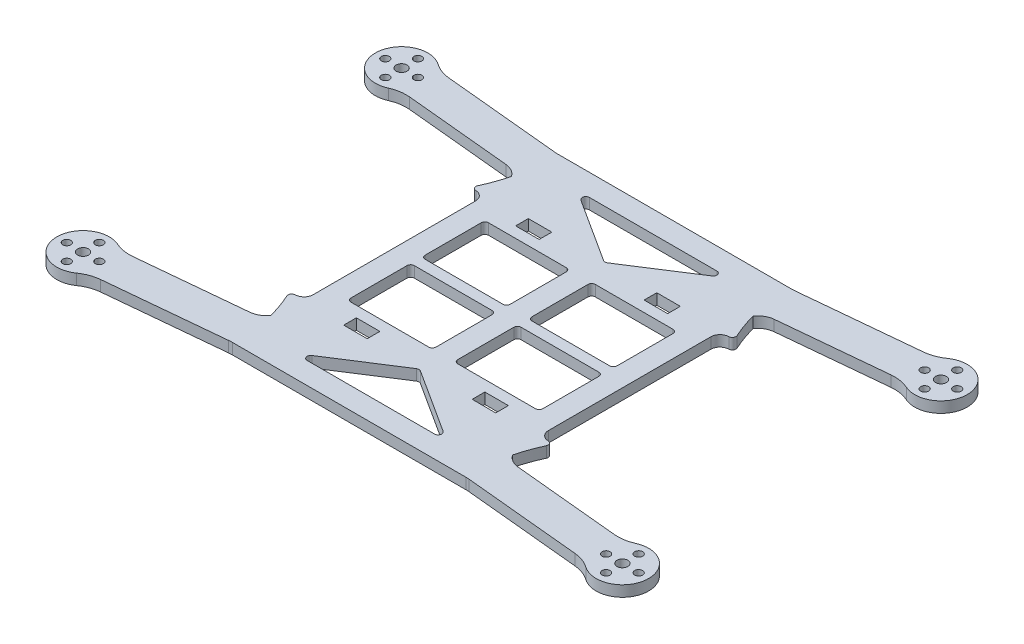
SolidWorks part; units mm, degrees
material "PLA"
ref_plane "Front Plane" through (0, 0, 0) normal (0, 0, 1) x (1, 0, 0)
ref_plane "Top Plane" through (0, 0, 0) normal (0, 1, 0) x (1, 0, 0)
ref_plane "Right Plane" through (0, 0, 0) normal (1, 0, 0) x (0, 0, -1)
sketch "Sketch1" plane through (0, 0, 0) normal (0, 1, 0) x (1, 0, 0)
  line L0 (-65.5414, 48.1601) -> (-33.2187, 45.0461)
  line L1 (-32.2597, -45) -> (32.2597, -45)
  line L2 (-32.5, -22.4419) -> (-32.5, 22.4419)
  line L3 (-32.2597, 45) -> (32.2597, 45)
  line L4 (32.5, -22.4419) -> (32.5, 22.4419)
  line L5 (0, 45) -> (0, -45) construction
  line L6 (-32.5, 0) -> (32.5, 0) construction
  line L7 (-66.5004, 38.2062) -> (-37.0205, 35.3661)
  line L8 (-74.5, 44) -> (-32.5933, 39.9627) construction
  line L9 (-74.5, -44) -> (-32.5933, -39.9627) construction
  line L10 (0, -55) -> (0, 55) construction
  line L11 (-66.5004, -38.2062) -> (-37.0205, -35.3661)
  line L12 (-65.5414, -48.1601) -> (-33.2187, -45.0461)
  line L13 (74.5, -44) -> (32.5933, -39.9627) construction
  line L14 (65.5414, -48.1601) -> (33.2187, -45.0461)
  line L15 (66.5004, -38.2062) -> (37.0205, -35.3661)
  line L16 (74.5, 44) -> (32.5933, 39.9627) construction
  line L17 (66.5004, 38.2062) -> (37.0205, 35.3661)
  line L18 (65.5414, 48.1601) -> (33.2187, 45.0461)
  arc A34 (-70.3318, 49.932) -> (-71.5409, 37.3814) centre (-74.5, 44) ccw
  circle A35 centre (-74.5, 44) radius 4.5 construction
  circle A36 centre (-79, 44) radius 1.1
  circle A49 centre (79, -44) radius 1
  circle A55 centre (79, 44) radius 1.1
  arc A58 (-33.3868, 33.2319) -> (-37.0205, 35.3661) centre (-37.5, 30.3891) ccw
  arc A59 (-32.2597, 45) -> (-33.2187, 45.0461) centre (-32.2597, 55) cw
  circle A60 centre (-74.5, 48.5) radius 1.1
  circle A61 centre (-70, 44) radius 1.1
  circle A62 centre (-74.5, 39.5) radius 1.1
  arc A63 (-66.5004, 38.2062) -> (-71.5409, 37.3814) centre (-67.4593, 28.2522) ccw
  arc A64 (-70.3318, 49.932) -> (-65.5414, 48.1601) centre (-64.5824, 58.114) ccw
  arc A65 (-33.3868, -33.2319) -> (-37.0205, -35.3661) centre (-37.5, -30.3891) cw
  circle A66 centre (-74.5, -44) radius 4.5 construction
  arc A67 (-70.3318, -49.932) -> (-65.5414, -48.1601) centre (-64.5824, -58.114) cw
  arc A68 (-66.5004, -38.2062) -> (-71.5409, -37.3814) centre (-67.4593, -28.2522) cw
  circle A69 centre (-74.5, -39.5) radius 1.1
  circle A70 centre (-70, -44) radius 1.1
  circle A71 centre (-74.5, -48.5) radius 1.1
  arc A72 (-32.2597, -45) -> (-33.2187, -45.0461) centre (-32.2597, -55) ccw
  circle A73 centre (-79, -44) radius 1.1
  arc A74 (-70.3318, -49.932) -> (-71.5409, -37.3814) centre (-74.5, -44) cw
  circle A75 centre (74.5, -44) radius 4.5 construction
  arc A76 (70.3318, -49.932) -> (71.5409, -37.3814) centre (74.5, -44) ccw
  circle A77 centre (79, -44) radius 1.1
  arc A78 (32.2597, -45) -> (33.2187, -45.0461) centre (32.2597, -55) cw
  circle A79 centre (74.5, -48.5) radius 1.1
  circle A80 centre (70, -44) radius 1.1
  circle A81 centre (74.5, -39.5) radius 1.1
  arc A82 (66.5004, -38.2062) -> (71.5409, -37.3814) centre (67.4593, -28.2522) ccw
  arc A83 (70.3318, -49.932) -> (65.5414, -48.1601) centre (64.5824, -58.114) ccw
  arc A84 (33.3868, -33.2319) -> (37.0205, -35.3661) centre (37.5, -30.3891) ccw
  circle A85 centre (74.5, 44) radius 4.5 construction
  arc A86 (70.3318, 49.932) -> (65.5414, 48.1601) centre (64.5824, 58.114) cw
  arc A87 (66.5004, 38.2062) -> (71.5409, 37.3814) centre (67.4593, 28.2522) cw
  circle A88 centre (74.5, 39.5) radius 1.1
  circle A89 centre (70, 44) radius 1.1
  circle A90 centre (74.5, 48.5) radius 1.1
  arc A91 (32.2597, 45) -> (33.2187, 45.0461) centre (32.2597, 55) ccw
  arc A92 (33.3868, 33.2319) -> (37.0205, 35.3661) centre (37.5, 30.3891) cw
  circle A93 centre (79, 44) radius 1.1
  arc A94 (70.3318, 49.932) -> (71.5409, 37.3814) centre (74.5, 44) cw
  circle A95 centre (-74.5, -44) radius 1.5
  circle A96 centre (-74.5, 44) radius 1.5
  circle A97 centre (74.5, 44) radius 1.5
  circle A98 centre (74.5, -44) radius 1.5
  arc A99 (-35.8354, 26.3563) -> (-33.3868, 33.2319) centre (-74.5, 44) ccw
  arc A100 (-32.5, 22.4419) -> (-34.9469, 24.9414) centre (-35, 22.4419) ccw
  arc A101 (-35.8354, 26.3563) -> (-34.9469, 24.9414) centre (-34.9257, 25.9411) ccw
  arc A102 (35.8354, 26.3563) -> (33.3868, 33.2319) centre (74.5, 44) cw
  arc A103 (32.5, 22.4419) -> (34.9469, 24.9414) centre (35, 22.4419) cw
  arc A104 (35.8354, 26.3563) -> (34.9469, 24.9414) centre (34.9257, 25.9411) cw
  arc A105 (35.8354, -26.3563) -> (33.3868, -33.2319) centre (74.5, -44) ccw
  arc A106 (35.8354, -26.3563) -> (34.9469, -24.9414) centre (34.9257, -25.9411) ccw
  arc A107 (32.5, -22.4419) -> (34.9469, -24.9414) centre (35, -22.4419) ccw
  arc A108 (-35.8354, -26.3563) -> (-34.9469, -24.9414) centre (-34.9257, -25.9411) cw
  arc A109 (-32.5, -22.4419) -> (-34.9469, -24.9414) centre (-35, -22.4419) cw
  arc A110 (-35.8354, -26.3563) -> (-33.3868, -33.2319) centre (-74.5, -44) cw
  point P0 (0, 0)
  point P23 (-32.7403, 45)
  point P28 (-70, 70)
  point P40 (-74.5, 44)
  point P66 (-74.5, -44)
  point P68 (-70, -70)
  point P69 (-32.7403, -45)
  point P90 (32.7403, -45)
  point P91 (74.5, -44)
  point P113 (74.5, 44)
  point P114 (70, 70)
  point P115 (32.7403, 45)
  dimension "D3" = 44
  dimension "D5" = 45
  dimension "D8" = 14.5
  dimension "D9" = 10
  dimension "D10" = 3
  dimension "D4" = 64.5194
  dimension "D7" = 32.5
  dimension "D6" = 6.364
  dimension "D11" = 9
  dimension "D12" = 2.2
  dimension "D13" = 10
  dimension "D14" = 85
  dimension "D15" = 5
  dimension "D18" = 10
  dimension "D20" = 10
  dimension "D21" = 10
  dimension "D22" = 2
  dimension "D16" = 65
  dimension "D17" = 5
  dimension "D19" = 4
extrude "Boss-Extrude1" add sketch "Sketch1" along normal blind 3 contours A94 A86 L18 A91 L3 A59 L0 A64 A34 A63 L7 A58 L2 A65 L11 A68 A74 A67 L12 A72 L1 A78 L14 A83 A76 A82 L15 A84 L4 A92 L17 A87 A89 A73 A70 A55 A36 A49 A60 A61 A62
sketch "Sketch2" plane through (0, 3, 0) normal (0, 1, 0) x (1, 0, 0)
  line L0 (-55, 0) -> (55, 0) construction
  line L1 (-21, 25.5) -> (-14.5, 25.5)
  line L2 (-21, 25.5) -> (-21, 22)
  line L3 (-21, 22) -> (-14.5, 22)
  line L4 (-14.5, 25.5) -> (-14.5, 22)
  line L5 (-14.5, -25.5) -> (-14.5, -22)
  line L6 (-21, -22) -> (-14.5, -22)
  line L7 (-21, -25.5) -> (-21, -22)
  line L8 (-21, -25.5) -> (-14.5, -25.5)
  line L9 (0, -55) -> (0, 55) construction
  line L10 (21, -25.5) -> (14.5, -25.5)
  line L11 (21, -25.5) -> (21, -22)
  line L12 (21, -22) -> (14.5, -22)
  line L13 (14.5, -25.5) -> (14.5, -22)
  line L14 (14.5, 25.5) -> (14.5, 22)
  line L15 (21, 22) -> (14.5, 22)
  line L16 (21, 25.5) -> (21, 22)
  line L17 (21, 25.5) -> (14.5, 25.5)
  line L18 (-25.5, 19) -> (-4, 19)
  line L19 (-25.5, -1.5) -> (-4, -1.5)
  line L20 (-26.5, -2.5) -> (-26.5, -18)
  line L21 (-25.5, -19) -> (-4, -19)
  line L22 (-3, -2.5) -> (-3, -18)
  line L23 (-26.5, 18) -> (-26.5, 2.5)
  line L24 (-25.5, 1.5) -> (-4, 1.5)
  line L25 (-3, 18) -> (-3, 2.5)
  line L26 (4, 19) -> (25.5, 19)
  line L27 (3, 18) -> (3, 2.5)
  line L28 (4, 1.5) -> (25.5, 1.5)
  line L29 (26.5, 18) -> (26.5, 2.5)
  line L30 (4, -1.5) -> (25.5, -1.5)
  line L31 (3, -2.5) -> (3, -18)
  line L32 (4, -19) -> (25.5, -19)
  line L33 (26.5, -2.5) -> (26.5, -18)
  line L34 (-32.5, -22.4419) -> (-32.5, 22.4419) construction
  line L35 (32.5, -22.4419) -> (32.5, 22.4419) construction
  line L36 (-17.5952, 39) -> (17.5952, 39)
  line L37 (18.1359, 37.1588) -> (0.5408, 25.8476)
  line L38 (-0.5408, 25.8476) -> (-18.1359, 37.1588)
  line L39 (-32.2597, 45) -> (32.2597, 45) construction
  line L40 (-17.5952, -39) -> (17.5952, -39)
  line L41 (18.1359, -37.1588) -> (0.5408, -25.8476)
  line L42 (-0.5408, -25.8476) -> (-18.1359, -37.1588)
  line L43 (-32.2597, -45) -> (32.2597, -45) construction
  arc A0 (0.5408, -25.8476) -> (-0.5408, -25.8476) centre (0, -26.6888) ccw
  arc A1 (17.5952, -39) -> (18.1359, -37.1588) centre (17.5952, -38) ccw
  arc A2 (-17.5952, -39) -> (-18.1359, -37.1588) centre (-17.5952, -38) cw
  arc A3 (26.5, -18) -> (25.5, -19) centre (25.5, -18) cw
  arc A4 (26.5, -2.5) -> (25.5, -1.5) centre (25.5, -2.5) ccw
  arc A5 (3, -2.5) -> (4, -1.5) centre (4, -2.5) cw
  arc A6 (3, -18) -> (4, -19) centre (4, -18) ccw
  arc A7 (-25.5, -19) -> (-26.5, -18) centre (-25.5, -18) cw
  arc A8 (-3, -18) -> (-4, -19) centre (-4, -18) cw
  arc A9 (-3, -2.5) -> (-4, -1.5) centre (-4, -2.5) ccw
  arc A10 (-25.5, -1.5) -> (-26.5, -2.5) centre (-25.5, -2.5) ccw
  arc A11 (-25.5, 1.5) -> (-26.5, 2.5) centre (-25.5, 2.5) cw
  arc A12 (-3, 18) -> (-4, 19) centre (-4, 18) ccw
  arc A13 (-26.5, 18) -> (-25.5, 19) centre (-25.5, 18) cw
  arc A14 (-3, 2.5) -> (-4, 1.5) centre (-4, 2.5) cw
  arc A15 (3, 2.5) -> (4, 1.5) centre (4, 2.5) ccw
  arc A16 (26.5, 2.5) -> (25.5, 1.5) centre (25.5, 2.5) cw
  arc A17 (26.5, 18) -> (25.5, 19) centre (25.5, 18) ccw
  arc A18 (4, 19) -> (3, 18) centre (4, 18) ccw
  arc A19 (18.1359, 37.1588) -> (17.5952, 39) centre (17.5952, 38) ccw
  arc A20 (-17.5952, 39) -> (-18.1359, 37.1588) centre (-17.5952, 38) ccw
  arc A21 (0.5408, 25.8476) -> (-0.5408, 25.8476) centre (0, 26.6888) cw
  point P53 (0, -25.5)
  point P56 (21, -39)
  point P59 (-21, -39)
  point P68 (3, -19)
  point P73 (-3, -19)
  point P96 (21, 39)
  point P99 (-21, 39)
  point P102 (0, 25.5)
  dimension "D21" = 1
  dimension "D1" = 3.5
  dimension "D2" = 6.5
  dimension "D3" = 14.5
  dimension "D4" = 22
  dimension "D5" = 6
  dimension "D6" = 6
  dimension "D7" = 6
  dimension "D8" = 3
  dimension "D9" = 3
  dimension "D10" = 3
  dimension "D11" = 3
  dimension "D12" = 6
  dimension "D13" = 3
  dimension "D14" = 3
  dimension "D15" = 6
  dimension "D16" = 6
  dimension "D17" = 3
  dimension "D18" = 1.5
  dimension "D19" = 1.5
  dimension "D20" = 6
  dimension "D23" = 42
  dimension "D24" = 6
extrude "Cut-Extrude1" cut sketch "Sketch2" against normal blind 3
